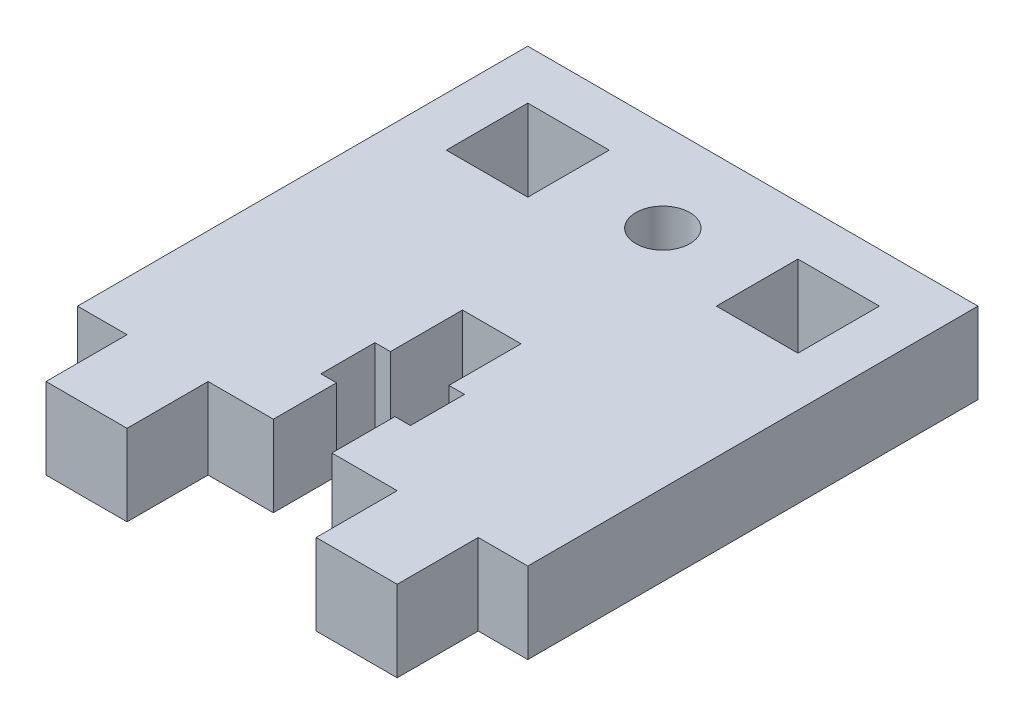
SolidWorks part; units mm, degrees
ref_plane "Front Plane" through (0, 0, 0) normal (0, 0, 1) x (1, 0, 0)
ref_plane "Top Plane" through (0, 0, 0) normal (0, 1, 0) x (1, 0, 0)
ref_plane "Right Plane" through (0, 0, 0) normal (1, 0, 0) x (0, 0, -1)
sketch "Sketch1" plane through (0, 0, 0) normal (0, 1, 0) x (1, 0, 0)
  line L0 (-25, 25) -> (25, -25) construction
  line L1 (-25, -25) -> (25, -25)
  line L2 (-25, -25) -> (-25, 25)
  line L3 (-25, 25) -> (25, 25)
  line L4 (25, -25) -> (25, 25)
  line L5 (-25, -25) -> (25, 25) construction
  line B0 (-19.5, -25) -> (-19.5, -34)
  line B1 (-19.5, -34) -> (-10.5, -34)
  line B2 (-10.5, -34) -> (-10.5, -25)
  line B3 (-10.5, -25) -> (-3.25, -25)
  line B4 (-3.25, -25) -> (-3.25, -18)
  line B5 (-3.25, -18) -> (-4.975, -18)
  line B6 (-4.975, -18) -> (-4.975, -12)
  line B7 (-4.975, -12) -> (-3.25, -12)
  line B8 (-3.25, -12) -> (-3.25, -4)
  line B9 (-3.25, -4) -> (3.25, -4)
  line B10 (0, -4) -> (0, -25) construction
  line B11 (3.25, -12) -> (3.25, -4)
  line B12 (4.975, -12) -> (3.25, -12)
  line B13 (4.975, -18) -> (4.975, -12)
  line B14 (3.25, -18) -> (4.975, -18)
  line B15 (3.25, -25) -> (3.25, -18)
  line B16 (10.5, -25) -> (3.25, -25)
  line B17 (10.5, -34) -> (10.5, -25)
  line B18 (19.5, -34) -> (10.5, -34)
  line B19 (19.5, -25) -> (19.5, -34)
  line B20 (0, 15) -> (-15, 15) construction
  line B21 (0, 20.4701) -> (0, 9.9881) construction
  line B22 (19.525, 19.525) -> (10.475, 19.525)
  line B23 (-19.525, 10.475) -> (-10.475, 10.475)
  line B24 (-19.525, 10.475) -> (-19.525, 19.525)
  line B25 (-19.525, 19.525) -> (-10.475, 19.525)
  line B26 (-10.475, 10.475) -> (-10.475, 19.525)
  line B27 (-19.525, 10.475) -> (-10.475, 19.525) construction
  line B28 (-19.525, 19.525) -> (-10.475, 10.475) construction
  line B29 (10.475, 10.475) -> (10.475, 19.525)
  line B30 (19.525, 10.475) -> (10.475, 10.475)
  line B31 (19.525, 10.475) -> (19.525, 19.525)
  circle B32 centre (0, 15) radius 3
  dimension "D1" = 50
  dimension "D2" = 50
  dimension "D3" = 15
sketch_block_instance "Plot_9mm_M6_bois-1"
sketch_block "Plot_9mm_M6_bois" parameters "D1"=9, "D2"=9, "D3"=16, "D4"=30, "D5"=9.95, "D6"=6.5, "D7"=6, "D8"=8
sketch_block_instance "Insert_9mm_M6_bois-1"
sketch_block "Insert_9mm_M6_bois" parameters "D4"=6, "D1"=9.05, "D2"=9.05, "D3"=15
extrude "Boss-Extrude1" add sketch "Sketch1" along normal blind 9 contours B15 L1 L4 L3 L2 B4 B5 B6 B7 B8 B9 B11 B12 B13 B14 B32 B31 B30 B29 B22 B26 B23 B24 B25 | B1 B2 L1 B0 | B19 L1 B17 B18
